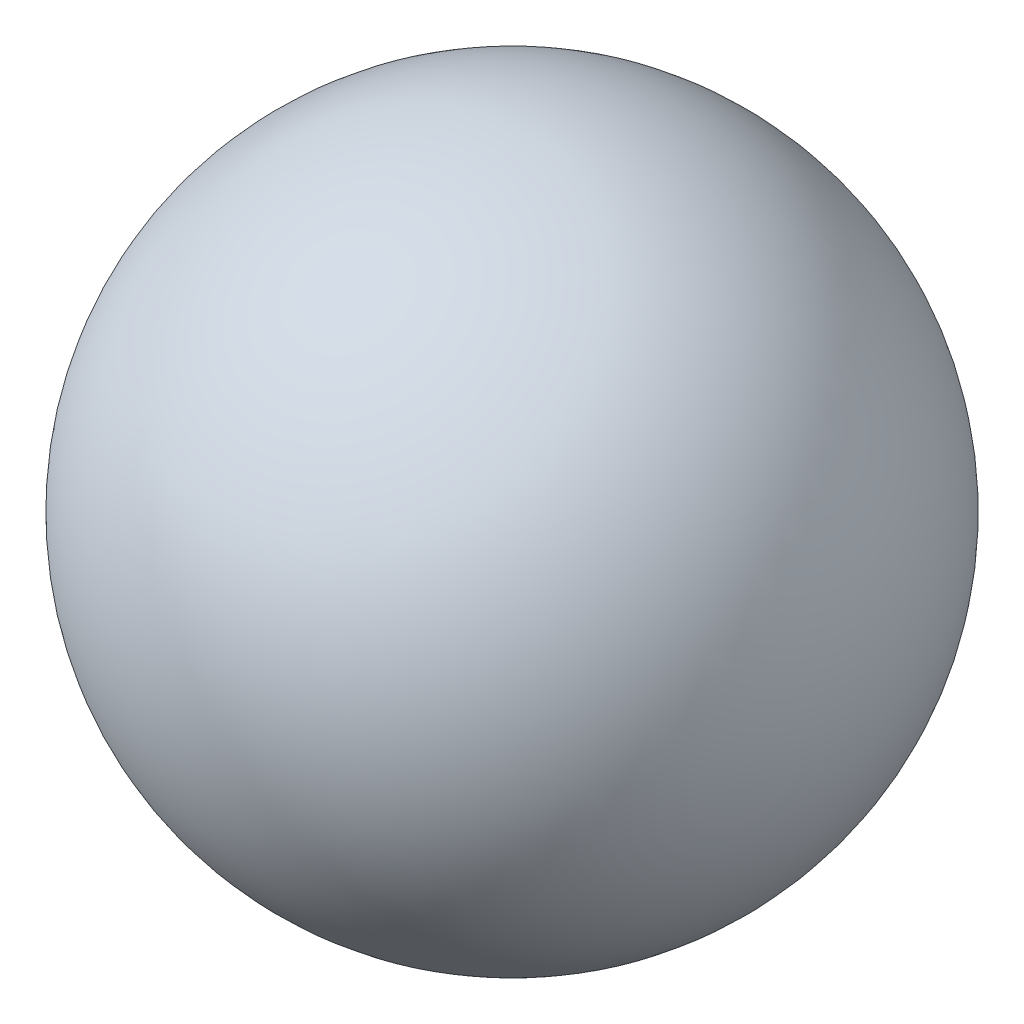
SolidWorks part; units mm, degrees
ref_plane "Front Plane" through (0, 0, 0) normal (0, 0, 1) x (1, 0, 0)
ref_plane "Top Plane" through (0, 0, 0) normal (0, 1, 0) x (1, 0, 0)
ref_plane "Right Plane" through (0, 0, 0) normal (1, 0, 0) x (0, 0, -1)
sketch "Sketch1" plane through (0, 0, 0) normal (0, 0, 1) x (1, 0, 0)
  line L0 (0, 38.5) -> (0, -38.5)
  arc A0 (0, 38.5) -> (0, -38.5) centre (0, 0) ccw
  dimension "D1" = 77
revolve "Revolve1" add sketch "Sketch1" angle 360 about L0
